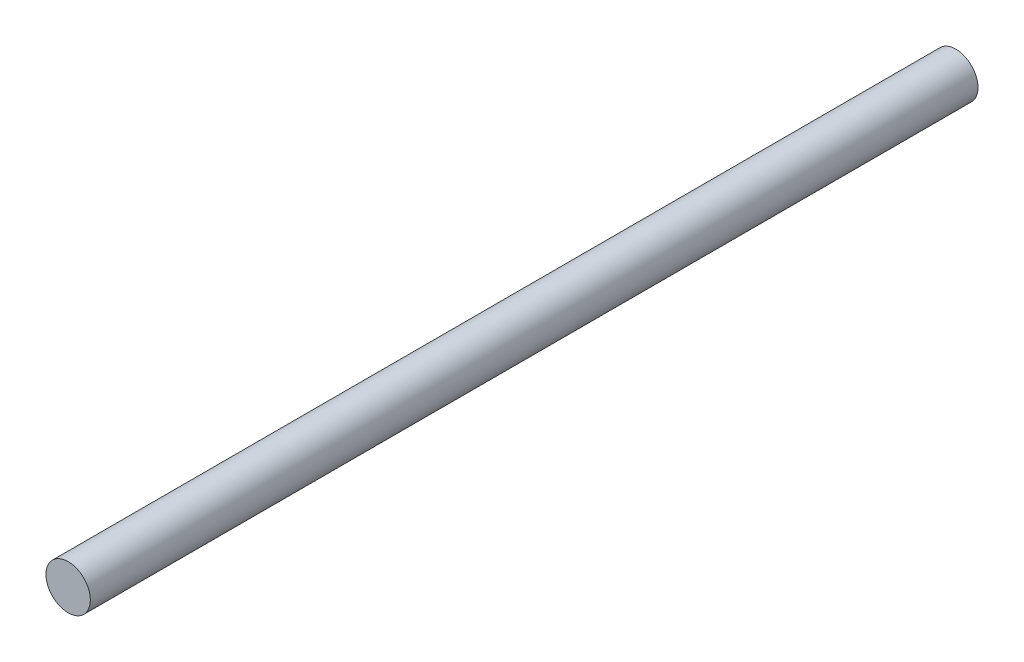
SolidWorks part; units mm, degrees
material "6061-T6 (SS)"
ref_plane "Front Plane" through (0, 0, 0) normal (0, 0, 1) x (1, 0, 0)
ref_plane "Top Plane" through (0, 0, 0) normal (0, 1, 0) x (1, 0, 0)
ref_plane "Right Plane" through (0, 0, 0) normal (1, 0, 0) x (0, 0, -1)
sketch "Sketch1" plane through (0, 0, 0) normal (0, 0, 1) x (1, 0, 0)
  circle A0 centre (0, 0) radius 1.5875
  dimension "D1" = 3.175
extrude "Boss-Extrude1" add sketch "Sketch1" along normal blind 63.5
